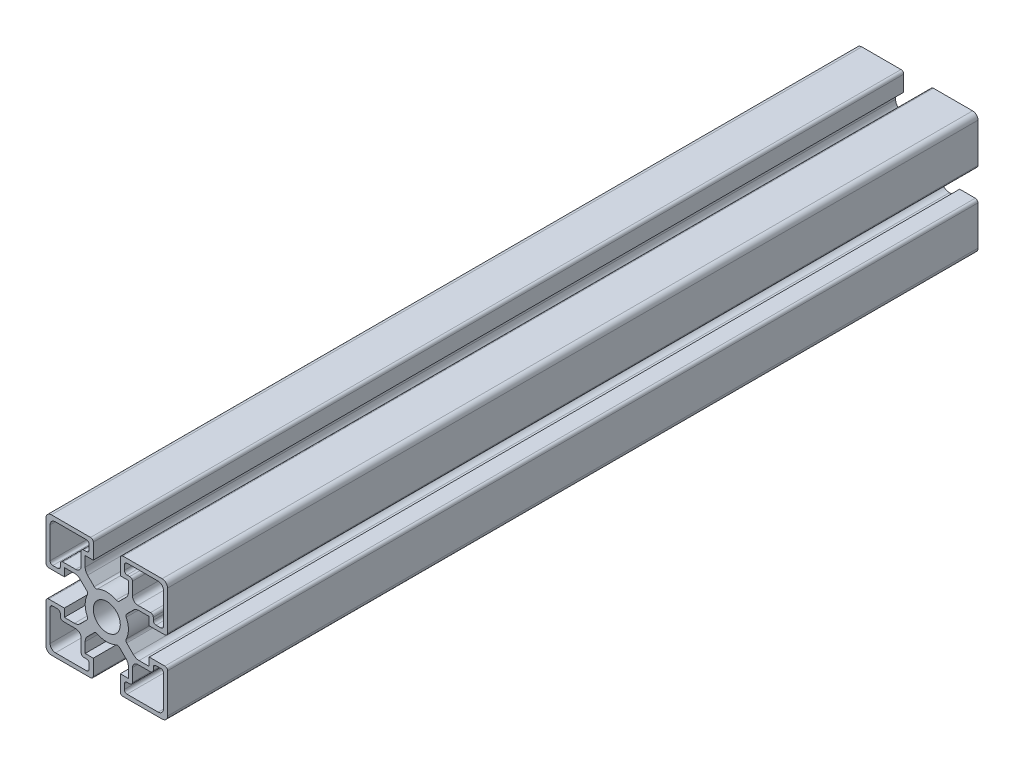
SolidWorks part; units mm, degrees
ref_plane "Front Plane" through (0, 0, 0) normal (0, 0, 1) x (1, 0, 0)
ref_plane "Top Plane" through (0, 0, 0) normal (0, 1, 0) x (1, 0, 0)
ref_plane "Right Plane" through (0, 0, 0) normal (1, 0, 0) x (0, 0, -1)
sketch "Sketch1" plane through (0, 0, 0) normal (0, 0, 1) x (1, 0, 0)
  line L0 (-5, -15.7059) -> (-8, -15.7059)
  line L1 (-20.5, -22.5) -> (-6, -22.5)
  line L2 (-22.5, -20.5) -> (-22.5, -6)
  line L5 (-21.9142, -21.9142) -> (22.5, 22.5) construction
  line L6 (-22.5, 22.5) -> (22.5, -22.5) construction
  line L7 (-20.5, -22.5) -> (-6, -22.5)
  line L8 (-22.5, -20.5) -> (-22.5, -6)
  line L10 (-5, -21.5) -> (-5, -15.7059)
  line L11 (-8, -15.7059) -> (-8, -11.9485)
  line L12 (-7.1213, -9.8272) -> (-4.6684, -7.3742)
  line L14 (-19, -21) -> (-7.5, -21)
  line L15 (-6.5, -20) -> (-6.5, -18.2059)
  line L16 (-7.5, -17.2059) -> (-8.5, -17.2059)
  line L17 (-9.5, -16.2059) -> (-9.5, -11.5)
  line L18 (-16.2059, -9.5) -> (-11.5, -9.5)
  line L19 (-17.2059, -7.5) -> (-17.2059, -8.5)
  line L20 (-20, -6.5) -> (-18.2059, -6.5)
  line L21 (-21, -19) -> (-21, -7.5)
  line L22 (-9.8272, -7.1213) -> (-7.3742, -4.6684)
  line L23 (-15.7059, -8) -> (-11.9485, -8)
  line L24 (-15.7059, -5) -> (-15.7059, -8)
  line L25 (-21.5, -5) -> (-15.7059, -5)
  line L26 (0, 27.7778) -> (0, -29.5537) construction
  line L27 (-31.2741, 0) -> (30.8136, 0) construction
  line L28 (-9.5, 16.2059) -> (-9.5, 11.5)
  line L29 (-16.2059, 9.5) -> (-11.5, 9.5)
  line L30 (-17.2059, 7.5) -> (-17.2059, 8.5)
  line L31 (-20, 6.5) -> (-18.2059, 6.5)
  line L32 (-21, 19) -> (-21, 7.5)
  line L33 (-19, 21) -> (-7.5, 21)
  line L34 (-6.5, 20) -> (-6.5, 18.2059)
  line L35 (-7.5, 17.2059) -> (-8.5, 17.2059)
  line L36 (-22.5, 20.5) -> (-22.5, 6)
  line L37 (-20.5, 22.5) -> (-6, 22.5)
  line L38 (-5, 21.5) -> (-5, 15.7059)
  line L39 (-5, 15.7059) -> (-8, 15.7059)
  line L40 (-8, 15.7059) -> (-8, 11.9485)
  line L41 (-7.1213, 9.8272) -> (-4.6684, 7.3742)
  line L42 (-9.8272, 7.1213) -> (-7.3742, 4.6684)
  line L43 (-15.7059, 8) -> (-11.9485, 8)
  line L44 (-15.7059, 5) -> (-15.7059, 8)
  line L45 (-21.5, 5) -> (-15.7059, 5)
  line L46 (16.2059, 9.5) -> (11.5, 9.5)
  line L47 (9.5, 16.2059) -> (9.5, 11.5)
  line L48 (7.5, 17.2059) -> (8.5, 17.2059)
  line L49 (6.5, 20) -> (6.5, 18.2059)
  line L50 (19, 21) -> (7.5, 21)
  line L51 (21, 19) -> (21, 7.5)
  line L52 (20, 6.5) -> (18.2059, 6.5)
  line L53 (17.2059, 7.5) -> (17.2059, 8.5)
  line L54 (20.5, 22.5) -> (6, 22.5)
  line L55 (22.5, 20.5) -> (22.5, 6)
  line L56 (21.5, 5) -> (15.7059, 5)
  line L57 (15.7059, 5) -> (15.7059, 8)
  line L58 (15.7059, 8) -> (11.9485, 8)
  line L59 (9.8272, 7.1213) -> (7.3742, 4.6684)
  line L60 (7.1213, 9.8272) -> (4.6684, 7.3742)
  line L61 (8, 15.7059) -> (8, 11.9485)
  line L62 (5, 15.7059) -> (8, 15.7059)
  line L63 (5, 21.5) -> (5, 15.7059)
  line L64 (9.5, -16.2059) -> (9.5, -11.5)
  line L65 (16.2059, -9.5) -> (11.5, -9.5)
  line L66 (17.2059, -7.5) -> (17.2059, -8.5)
  line L67 (20, -6.5) -> (18.2059, -6.5)
  line L68 (21, -19) -> (21, -7.5)
  line L69 (19, -21) -> (7.5, -21)
  line L70 (6.5, -20) -> (6.5, -18.2059)
  line L71 (7.5, -17.2059) -> (8.5, -17.2059)
  line L72 (22.5, -20.5) -> (22.5, -6)
  line L73 (20.5, -22.5) -> (6, -22.5)
  line L74 (5, -21.5) -> (5, -15.7059)
  line L75 (5, -15.7059) -> (8, -15.7059)
  line L76 (8, -15.7059) -> (8, -11.9485)
  line L77 (7.1213, -9.8272) -> (4.6684, -7.3742)
  line L78 (9.8272, -7.1213) -> (7.3742, -4.6684)
  line L79 (15.7059, -8) -> (11.9485, -8)
  line L80 (15.7059, -5) -> (15.7059, -8)
  line L81 (21.5, -5) -> (15.7059, -5)
  circle A0 centre (0, 0) radius 5
  arc A1 (-3.5211, -7.1834) -> (3.5211, -7.1834) centre (0, 0) ccw
  arc A2 (-3.5211, -7.1834) -> (-4.6684, -7.3742) centre (-3.9613, -8.0814) ccw
  arc A3 (-8, -11.9485) -> (-7.1213, -9.8272) centre (-5, -11.9485) cw
  arc A4 (-6, -22.5) -> (-5, -21.5) centre (-6, -21.5) ccw
  arc A5 (-8.5, -17.2059) -> (-9.5, -16.2059) centre (-8.5, -16.2059) cw
  arc A6 (-6.5, -18.2059) -> (-7.5, -17.2059) centre (-7.5, -18.2059) ccw
  arc A7 (-6.5, -20) -> (-7.5, -21) centre (-7.5, -20) cw
  arc A8 (-17.2059, -8.5) -> (-16.2059, -9.5) centre (-16.2059, -8.5) ccw
  arc A9 (-18.2059, -6.5) -> (-17.2059, -7.5) centre (-18.2059, -7.5) cw
  arc A10 (-20, -6.5) -> (-21, -7.5) centre (-20, -7.5) ccw
  arc A11 (-22.5, -20.5) -> (-20.5, -22.5) centre (-20.5, -20.5) ccw
  arc A12 (-9.5, -11.5) -> (-11.5, -9.5) centre (-11.5, -11.5) ccw
  arc A13 (-19, -21) -> (-21, -19) centre (-19, -19) cw
  arc A14 (-7.1834, -3.5211) -> (-7.3742, -4.6684) centre (-8.0814, -3.9613) cw
  arc A15 (-11.9485, -8) -> (-9.8272, -7.1213) centre (-11.9485, -5) ccw
  arc A16 (-22.5, -6) -> (-21.5, -5) centre (-21.5, -6) cw
  arc A17 (-11.5, 9.5) -> (-9.5, 11.5) centre (-11.5, 11.5) ccw
  arc A18 (-17.2059, 8.5) -> (-16.2059, 9.5) centre (-16.2059, 8.5) cw
  arc A19 (-18.2059, 6.5) -> (-17.2059, 7.5) centre (-18.2059, 7.5) ccw
  arc A20 (-20, 6.5) -> (-21, 7.5) centre (-20, 7.5) cw
  arc A21 (-21, 19) -> (-19, 21) centre (-19, 19) cw
  arc A22 (-6.5, 20) -> (-7.5, 21) centre (-7.5, 20) ccw
  arc A23 (-6.5, 18.2059) -> (-7.5, 17.2059) centre (-7.5, 18.2059) cw
  arc A24 (-8.5, 17.2059) -> (-9.5, 16.2059) centre (-8.5, 16.2059) ccw
  arc A25 (-20.5, 22.5) -> (-22.5, 20.5) centre (-20.5, 20.5) ccw
  arc A26 (-6, 22.5) -> (-5, 21.5) centre (-6, 21.5) cw
  arc A27 (-8, 11.9485) -> (-7.1213, 9.8272) centre (-5, 11.9485) ccw
  arc A28 (-3.5211, 7.1834) -> (-4.6684, 7.3742) centre (-3.9613, 8.0814) cw
  arc A29 (-7.1834, 3.5211) -> (-7.3742, 4.6684) centre (-8.0814, 3.9613) ccw
  arc A30 (-11.9485, 8) -> (-9.8272, 7.1213) centre (-11.9485, 5) cw
  arc A31 (-22.5, 6) -> (-21.5, 5) centre (-21.5, 6) ccw
  arc A32 (9.5, 11.5) -> (11.5, 9.5) centre (11.5, 11.5) ccw
  arc A33 (8.5, 17.2059) -> (9.5, 16.2059) centre (8.5, 16.2059) cw
  arc A34 (6.5, 18.2059) -> (7.5, 17.2059) centre (7.5, 18.2059) ccw
  arc A35 (6.5, 20) -> (7.5, 21) centre (7.5, 20) cw
  arc A36 (19, 21) -> (21, 19) centre (19, 19) cw
  arc A37 (20, 6.5) -> (21, 7.5) centre (20, 7.5) ccw
  arc A38 (18.2059, 6.5) -> (17.2059, 7.5) centre (18.2059, 7.5) cw
  arc A39 (17.2059, 8.5) -> (16.2059, 9.5) centre (16.2059, 8.5) ccw
  arc A40 (22.5, 20.5) -> (20.5, 22.5) centre (20.5, 20.5) ccw
  arc A41 (22.5, 6) -> (21.5, 5) centre (21.5, 6) cw
  arc A42 (11.9485, 8) -> (9.8272, 7.1213) centre (11.9485, 5) ccw
  arc A43 (7.1834, 3.5211) -> (7.3742, 4.6684) centre (8.0814, 3.9613) cw
  arc A44 (3.5211, 7.1834) -> (4.6684, 7.3742) centre (3.9613, 8.0814) ccw
  arc A45 (8, 11.9485) -> (7.1213, 9.8272) centre (5, 11.9485) cw
  arc A46 (6, 22.5) -> (5, 21.5) centre (6, 21.5) ccw
  arc A47 (11.5, -9.5) -> (9.5, -11.5) centre (11.5, -11.5) ccw
  arc A48 (17.2059, -8.5) -> (16.2059, -9.5) centre (16.2059, -8.5) cw
  arc A49 (18.2059, -6.5) -> (17.2059, -7.5) centre (18.2059, -7.5) ccw
  arc A50 (20, -6.5) -> (21, -7.5) centre (20, -7.5) cw
  arc A51 (21, -19) -> (19, -21) centre (19, -19) cw
  arc A52 (6.5, -20) -> (7.5, -21) centre (7.5, -20) ccw
  arc A53 (6.5, -18.2059) -> (7.5, -17.2059) centre (7.5, -18.2059) cw
  arc A54 (8.5, -17.2059) -> (9.5, -16.2059) centre (8.5, -16.2059) ccw
  arc A55 (20.5, -22.5) -> (22.5, -20.5) centre (20.5, -20.5) ccw
  arc A56 (6, -22.5) -> (5, -21.5) centre (6, -21.5) cw
  arc A57 (8, -11.9485) -> (7.1213, -9.8272) centre (5, -11.9485) ccw
  arc A58 (3.5211, -7.1834) -> (4.6684, -7.3742) centre (3.9613, -8.0814) cw
  arc A59 (7.1834, -3.5211) -> (7.3742, -4.6684) centre (8.0814, -3.9613) ccw
  arc A60 (11.9485, -8) -> (9.8272, -7.1213) centre (11.9485, -5) cw
  arc A61 (22.5, -6) -> (21.5, -5) centre (21.5, -6) ccw
  arc A62 (-7.1834, 3.5211) -> (-7.1834, -3.5211) centre (0, 0) ccw
  arc A63 (3.5211, 7.1834) -> (-3.5211, 7.1834) centre (0, 0) ccw
  arc A64 (7.1834, -3.5211) -> (7.1834, 3.5211) centre (0, 0) ccw
  point P0 (0, 0)
  point P19 (-8, -10.7059)
  point P48 (-9.5, -9.5)
  point P51 (-21, -21)
  point P214 (0, 0)
  dimension "D3" = 17.5
  dimension "D5" = 1
  dimension "D6" = 3
  dimension "D2" = 1
  dimension "D11" = 1
  dimension "D12" = 2
  dimension "D1" = 45
  dimension "D4" = 5
  dimension "D7" = 1.5
  dimension "D8" = 1.5
  dimension "D9" = 1.5
  dimension "D10" = 1.5
  dimension "D13" = 4
extrude "Boss-Extrude1" add sketch "Sketch1" along normal blind 300 contours A59 A64 A43 L59 A42 L58 L57 L56 A41 L55 A40 L54 A46 L63 L62 L61 A45 L60 A44 A63 A28 L41 A27 L40 L39 L38 A26 L37 A25 L36 A31 L45 L44 L43 A30 L42 A29 A62 A14 L22 A15 L23 L24 L25 A16 L2 A11 L1 A4 L10 L0
sketch "Sketch2" plane through (0, 0, 0) normal (0, 1, 0) x (1, 0, 0)
  line L0 (0, 65.1913) -> (0, -377.1133) construction
